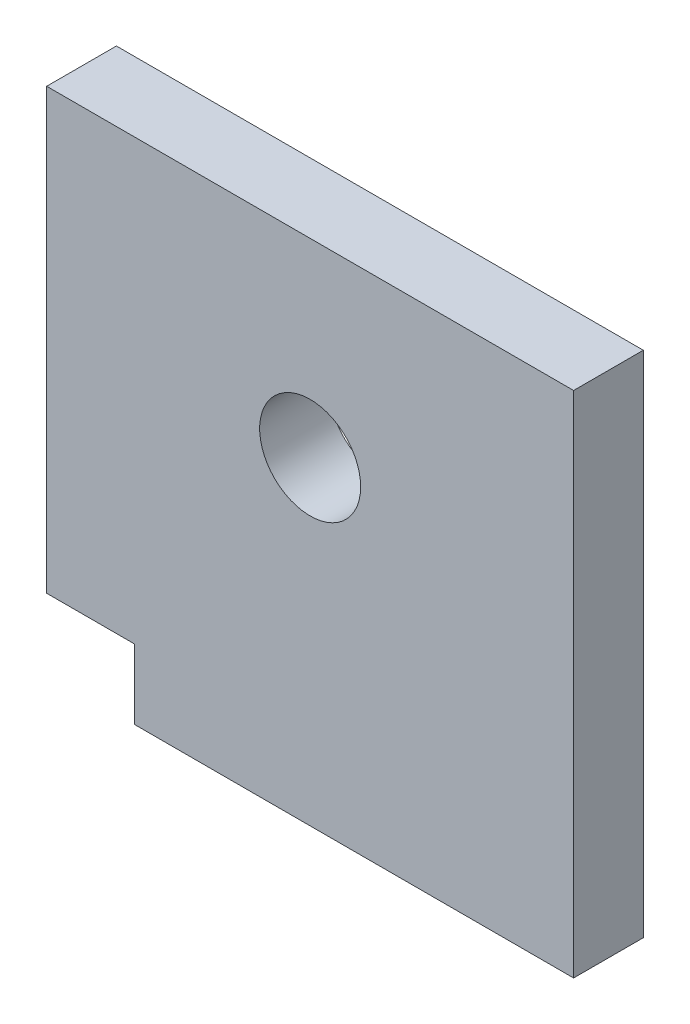
SolidWorks part; units mm, degrees
ref_plane "Front Plane" through (0, 0, 0) normal (0, 0, 1) x (1, 0, 0)
ref_plane "Top Plane" through (0, 0, 0) normal (0, 1, 0) x (1, 0, 0)
ref_plane "Right Plane" through (0, 0, 0) normal (1, 0, 0) x (0, 0, -1)
sketch "Sketch1" plane through (0, 0, 0) normal (0, 0, 1) x (1, 0, 0)
  line L1 (4, 0) -> (24, 0) construction
  line L2 (0, 0) -> (0, 20)
  line L3 (0, 20) -> (24, 20)
  line L4 (24, 0) -> (24, 20)
  line L6 (4, -3.175) -> (4, 0)
  line L7 (4, 0) -> (0, 0)
  line L8 (12, 20) -> (12, 0) construction
  line L9 (4, -3.175) -> (24, -3.175)
  line L10 (24, -3.175) -> (24, 0)
  circle A1 centre (12, 11.35) radius 2.3
  dimension "D5" = 4.6
  dimension "D6" = 11.35
  dimension "D1" = 24
  dimension "D2" = 4
  dimension "D3" = 3.175
  dimension "D4" = 20
extrude "Boss-Extrude1" add sketch "Sketch1" along normal blind 3.175
